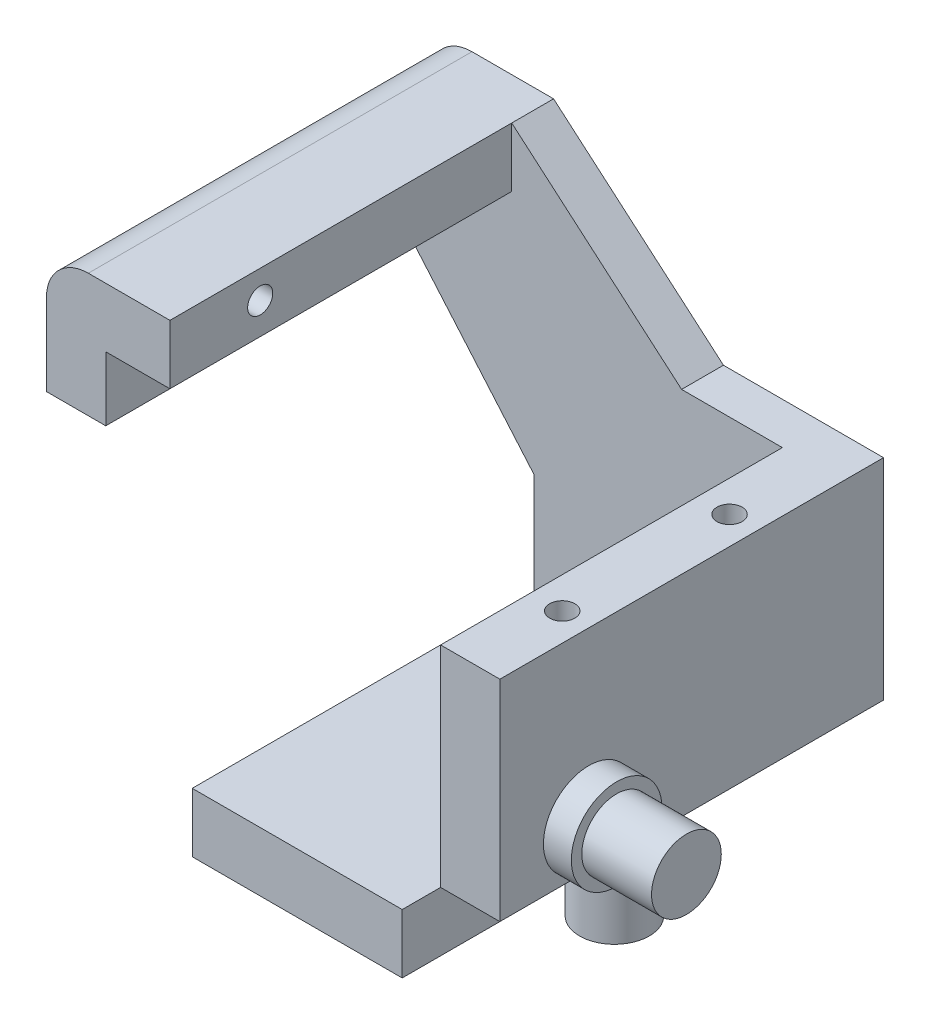
SolidWorks part; units mm, degrees
ref_plane "前视基准面" through (0, 0, 0) normal (0, 0, 1) x (1, 0, 0)
ref_plane "上视基准面" through (0, 0, 0) normal (0, 1, 0) x (1, 0, 0)
ref_plane "右视基准面" through (0, 0, 0) normal (1, 0, 0) x (0, 0, -1)
sketch "草图1" plane through (0, 0, 0) normal (0, 0, 1) x (1, 0, 0)
  line L1 (-16.25, -16.25) -> (16.25, -16.25)
  line L2 (-16.25, -16.25) -> (-16.25, 13.25)
  line L3 (-13.25, 16.25) -> (16.25, 16.25)
  line L4 (16.25, -16.25) -> (16.25, 16.25)
  arc A0 (-13.25, 16.25) -> (-16.25, 13.25) centre (-13.25, 13.25) ccw
  dimension "D1" = 3
extrude "凸台-拉伸1" add sketch "草图1" along normal blind 27.5
sketch "草图3" plane through (0, 0, 27.5) normal (0, 0, 1) x (1, 0, 0)
  line L1 (-12, -12) -> (12, -12)
  line L2 (-12, -12) -> (-12, 12)
  line L3 (-12, 12) -> (12, 12)
  line L4 (12, -12) -> (12, 12)
extrude "切除-拉伸3" cut sketch "草图3" against normal blind 24.5
sketch "草图4" plane through (0, 0, 27.5) normal (0, 0, 1) x (1, 0, 0)
  line L0 (-16.25, 16.25) -> (16.25, -16.25)
  line L1 (16.25, 16.25) -> (-7.4, 16.25)
  line L2 (16.25, 16.25) -> (16.25, 5.8)
  line L3 (16.25, 5.8) -> (-0.175, 5.8)
  line L5 (-7.4, 16.25) -> (-7.4, 12)
  line L7 (12, 12) -> (-12, 12) construction
  line L8 (-7.4, 12) -> (-0.175, 5.8)
extrude "切除-拉伸4" cut sketch "草图4" along direction (0, 0, -1) on the side against the normal blind 24.5 contours L3 L8 L5 L1 L2
ref_plane "基准面3" through (0, 0, 0) normal (0.7071, 0.7071, 0) x (0.7071, -0.7071, 0)
mirror "镜向1" about plane through (0, 0, 0) normal (0.7071, 0.7071, 0) of "切除-拉伸4"
sketch "草图6" plane through (0, 0, 0) normal (0, 0, -1) x (-1, 0, 0)
  line L0 (10.695, 10.695) -> (-10.695, -10.695) construction
  line L1 (-16.25, -16.25) -> (-6, -16.25)
  line L2 (-16.25, -16.25) -> (-16.25, -6)
  line L3 (-16.25, -6) -> (-6, -6)
  line L4 (-6, -16.25) -> (-6, -6)
sketch "草图7" plane through (0, -16.25, 0) normal (0, -1, 0) x (1, 0, 0)
  line L0 (6, 0) -> (6, 9.04)
  circle A1 centre (6, 9.04) radius 3.25
  dimension "D1" = 6.5
extrude "凸台-拉伸4" add sketch "草图7" along normal blind 2 contours A1
sketch "草图10" plane through (16.25, 0, 0) normal (1, 0, 0) x (0, 0, -1)
  line L0 (0, -6) -> (-21.13, -6)
  line L1 (0, -16.25) -> (0, -6) construction
  line L2 (0, -16.25) -> (0, -6) construction
  circle A0 centre (-21.13, -6) radius 3.25
  dimension "D1" = 6.5
extrude "凸台-拉伸5" add sketch "草图10" along normal blind 2 contours A0
sketch "草图13" plane through (0, 0, 27.5) normal (0, 0, 1) x (1, 0, 0)
  line L1 (16.25, -16.25) -> (9.25, -16.25)
  line L2 (16.25, -16.25) -> (16.25, -9.25)
  line L3 (16.25, -9.25) -> (12, -9.25)
  line L4 (9.25, -16.25) -> (9.25, -12)
  arc A0 (12, -9.25) -> (9.25, -12) centre (12, -12) ccw
  dimension "D1" = 2.75
extrude "切除-拉伸6" cut sketch "草图13" against normal blind 27.5
sketch "草图14" plane through (0, 0, 3) normal (0, 0, 1) x (1, 0, 0)
  line L0 (16.25, 5.8) -> (4.7758, 5.8)
  line L1 (4.7758, 5.8) -> (-7.4, 16.25)
  line L2 (-7.4, 16.25) -> (16.25, 16.25)
  line L3 (16.25, 16.25) -> (16.25, 5.8)
extrude "切除-拉伸7" cut sketch "草图14" against normal blind 3
mirror "镜向3" about plane through (0, 0, 0) normal (0.7071, 0.7071, 0) of "切除-拉伸7"
sketch "草图16" plane through (0, 5.8, 0) normal (0, 1, 0) x (1, 0, 0)
  line L0 (16.25, 0) -> (14.25, 0)
  line L1 (4.7758, 0) -> (16.25, 0) construction
  line L2 (14.25, 0) -> (14.25, -9.04)
  line L3 (14.25, 0) -> (14.25, -21.03)
  circle A0 centre (14.25, -9.04) radius 0.9
  circle A1 centre (14.25, -21.03) radius 0.9
  dimension "D1" = 1.8
  dimension "D2" = 1.8
extrude "切除-拉伸10" cut sketch "草图16" against normal blind 6 contours A0 | A1
mirror "镜向4" about plane through (0, 0, 0) normal (0.7071, 0.7071, 0) of "切除-拉伸10"
sketch "草图17" plane through (-7.4, 0, 0) normal (1, 0, 0) x (0, 0, -1)
  line L0 (-27.5, 16.25) -> (-27.5, 14.25)
  line L1 (-27.5, 16.25) -> (-27.5, 12) construction
  line L2 (-27.5, 14.25) -> (-21.03, 14.25)
  line L3 (-27.5, 14.25) -> (-9.04, 14.25)
  circle A0 centre (-21.03, 14.25) radius 0.9
  circle A1 centre (-9.04, 14.25) radius 0.9
  dimension "D1" = 6.47
  dimension "D3" = 1.8
  dimension "D4" = 1.8
  dimension "D2" = 18.46
sketch "草图20" plane through (18.25, 0, 0) normal (1, 0, 0) x (0, 0, -1)
  circle A0 centre (-21.13, -6) radius 2.5
  dimension "D1" = 5
extrude "凸台-拉伸6" add sketch "草图20" along normal blind 5
sketch "草图25" plane through (0, -18.25, 0) normal (0, -1, 0) x (1, 0, 0)
  circle A0 centre (6, 9.04) radius 2.5
extrude "凸台-拉伸7" add sketch "草图25" along normal blind 5
sketch "草图26" plane through (0, 7.4, 0) normal (0, -1, 0) x (-1, 0, 0)
  line L1 (12, -3) -> (12, -27.5) construction
  line L2 (16.25, -27.5) -> (12, -27.5) construction
  circle A0 centre (14.25, -9.04) radius 0.9
  dimension "D1" = 2.25
  dimension "D2" = 18.46
sketch "草图27" plane through (-7.4, 0, 0) normal (1, 0, 0) x (0, 0, -1)
  line L0 (-3, 12) -> (-27.5, 12) construction
  line L1 (-27.5, 16.25) -> (-27.5, 12) construction
  circle A0 centre (-21.03, 14.25) radius 0.9
  dimension "D1" = 2.25
  dimension "D2" = 6.47
extrude "切除-拉伸13" cut sketch "草图27" against normal blind 6
extrude "切除-拉伸14" cut sketch "草图26" against normal blind 6 contours A0
